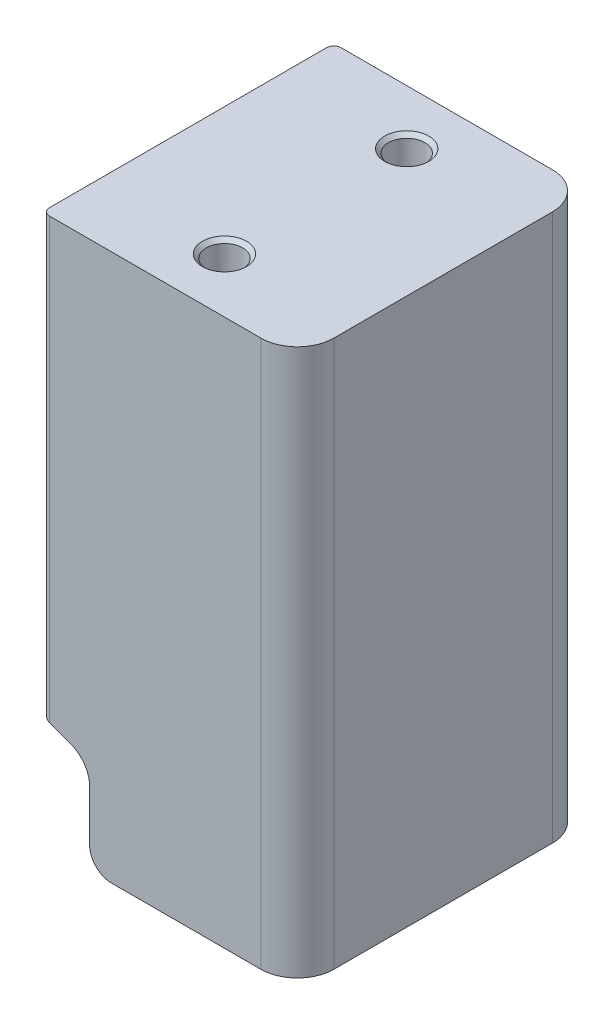
SolidWorks part; units mm, degrees
material "K110"
ref_plane "Front Plane" through (0, 0, 0) normal (0, 0, 1) x (1, 0, 0)
ref_plane "Top Plane" through (0, 0, 0) normal (0, 1, 0) x (1, 0, 0)
ref_plane "Right Plane" through (0, 0, 0) normal (1, 0, 0) x (0, 0, -1)
sketch "Sketch1" plane through (0, 0, 0) normal (0, 1, 0) x (1, 0, 0)
  line L1 (-17.5, -20) -> (17.5, -20)
  line L2 (-17.5, -20) -> (-17.5, 20)
  line L3 (-17.5, 20) -> (17.5, 20)
  line L4 (17.5, -20) -> (17.5, 20)
  line L5 (-17.5, -20) -> (17.5, 20) construction
  line L6 (-17.5, 20) -> (17.5, -20) construction
  point P0 (0, 0)
  dimension "D1" = 35
  dimension "D2" = 40
extrude "Boss-Extrude1" add sketch "Sketch1" against normal blind 75
sketch "Sketch2" plane through (0, 0, 20) normal (0, 0, 1) x (1, 0, 0)
  line L0 (-17.5, 0) -> (17.5, 0) construction
  line L1 (-17.5, -75) -> (-11, -75) construction
  line L2 (-17.5, -75) -> (-17.5, -61) construction
  line L3 (-17.5, -61) -> (-15, -61) construction
  line L4 (-11, -75) -> (-11, -65) construction
  line L5 (17.5, -75) -> (17.5, 0) construction
  line L6 (-13.6319, -61.2412) -> (-17.5, -59.8334)
  line L7 (-17.5, -75) -> (-17.5, 0) construction
  line L8 (-11, -65) -> (-11, -75)
  line L9 (-11, -75) -> (-17.5, -75)
  line L10 (-17.5, -75) -> (-17.5, -59.8334)
  arc A0 (-15, -61) -> (-11, -65) centre (-15, -65) cw construction
  arc A1 (-11, -65) -> (-13.6319, -61.2412) centre (-15, -65) ccw
  dimension "D3" = 4
  dimension "D1" = 61
  dimension "D2" = 28.5
  dimension "D4" = 2.5
  dimension "D5" = 20
extrude "Cut-Extrude1" cut sketch "Sketch2" against normal up to next
fillet "Fillet1" radius 3 1 edges at (-11, -75, 0)
fillet "Fillet2" radius 5 2 edges at (17.5, -37.5, -20) (17.5, -37.5, 20)
hole_wizard "M6 Tapped Hole1" positions "Sketch5" profile "Sketch4" tap size "M6" standard "ISO"
sketch "Sketch5" plane through (0, 0, 0) normal (0, 1, 0) x (1, 0, 0)
  line L0 (12.5, 20) -> (-17.5, 20) construction
  line L1 (-17.5, -20) -> (12.5, -20) construction
  point P0 (0, 12.5)
  point P2 (0, -12.5)
  dimension "D1" = 7.5
  dimension "D2" = 7.5
sketch "Sketch4" plane through (0, 0, -12.5) normal (1, 0, 0) x (0, 0, 1)
  line L0 (0, 0) -> (0, 18.5022)
  line L1 (0, 18.5022) -> (2.5, 17)
  line L2 (2.5, 17) -> (2.5, 0.525)
  line L3 (2.5, 0.525) -> (3.025, 0)
  line L5 (3.025, 0) -> (0, 0)
  line L6 (-2.5, 0.525) -> (-3.025, 0) construction
  line L10 (0, 18.5022) -> (-2.5, 17) construction
  line L11 (0, -6.35) -> (0, 107.95) construction
  dimension "Tap Drill Dia." = 5
  dimension "Tap Drill Depth" = 17
  dimension "Near C'Sink Dia." = 6.05
  dimension "Near C'Sink Angle" = 90
  dimension "Drill Angle" = 118
cosmetic thread "Hole Thread1" parameters "D1"=12, "D2"=6
cosmetic thread "Hole Thread2" parameters "D1"=12, "D2"=6
ref_plane "Plane1" through (0, -50, 0) normal (0, 1, 0) x (1, 0, 0)
sketch "Sketch6" plane through (0, -50, 0) normal (0, 1, 0) x (1, 0, 0)
  line L0 (-17.5, 20) -> (-17.5, -20)
  line L1 (-17.5, 20) -> (-17.5, -20)
  line L2 (-17.5, -20) -> (12.5, -20)
  line L3 (-17.5, -20) -> (12.5, -20)
  line L4 (17.5, -15) -> (17.5, 15)
  line L5 (17.5, -15) -> (17.5, 15)
  line L6 (12.5, 20) -> (-17.5, 20)
  line L7 (12.5, 20) -> (-17.5, 20)
  arc A0 (12.5, -20) -> (17.5, -15) centre (12.5, -15) ccw
  arc A1 (12.5, -20) -> (17.5, -15) centre (12.5, -15) ccw
  arc A2 (17.5, 15) -> (12.5, 20) centre (12.5, 15) ccw
  arc A3 (17.5, 15) -> (12.5, 20) centre (12.5, 15) ccw
fillet "Fillet3" radius 1 2 edges at (-17.5, -29.9167, -20) (-17.5, -29.9167, 20)
